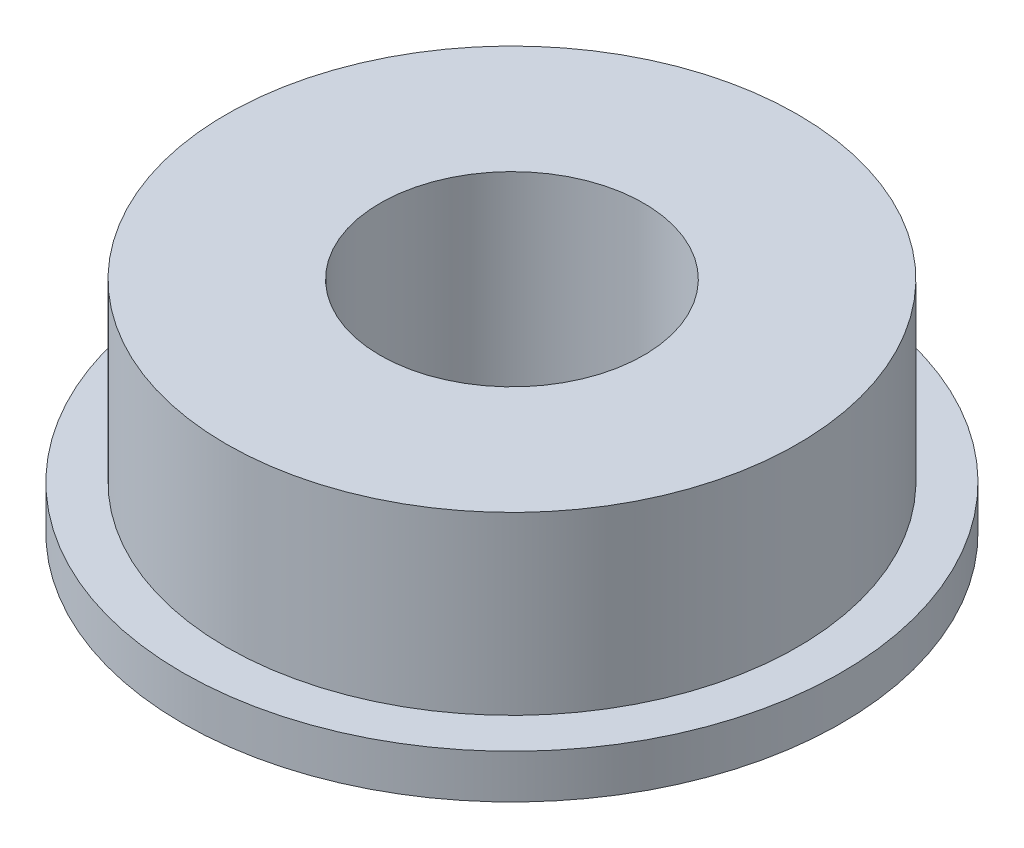
SolidWorks part; units mm, degrees
ref_plane "前视基准面" through (0, 0, 0) normal (0, 0, 1) x (1, 0, 0)
ref_plane "上视基准面" through (0, 0, 0) normal (0, 1, 0) x (1, 0, 0)
ref_plane "右视基准面" through (0, 0, 0) normal (1, 0, 0) x (0, 0, -1)
sketch "草图1" plane through (0, 0, 0) normal (0, 0, 1) x (1, 0, 0)
  line L0 (-3, 0.4625) -> (-7.5, 0.4625)
  line L1 (-7.5, 0.4625) -> (-7.5, 1.4625)
  line L2 (-7.5, 1.4625) -> (-6.5, 1.4625)
  line L3 (-6.5, 1.4625) -> (-6.5, 5.4625)
  line L4 (-6.5, 5.4625) -> (-3, 5.4625)
  line L5 (-3, 5.4625) -> (-3, 0.4625)
  line L6 (0, 11.1375) -> (0, -9.7875) construction
  dimension "D1" = 15
  dimension "D2" = 13
  dimension "D3" = 6
  dimension "D4" = 5
  dimension "D5" = 1
revolve "旋转1" add sketch "草图1" angle 360 about L6
